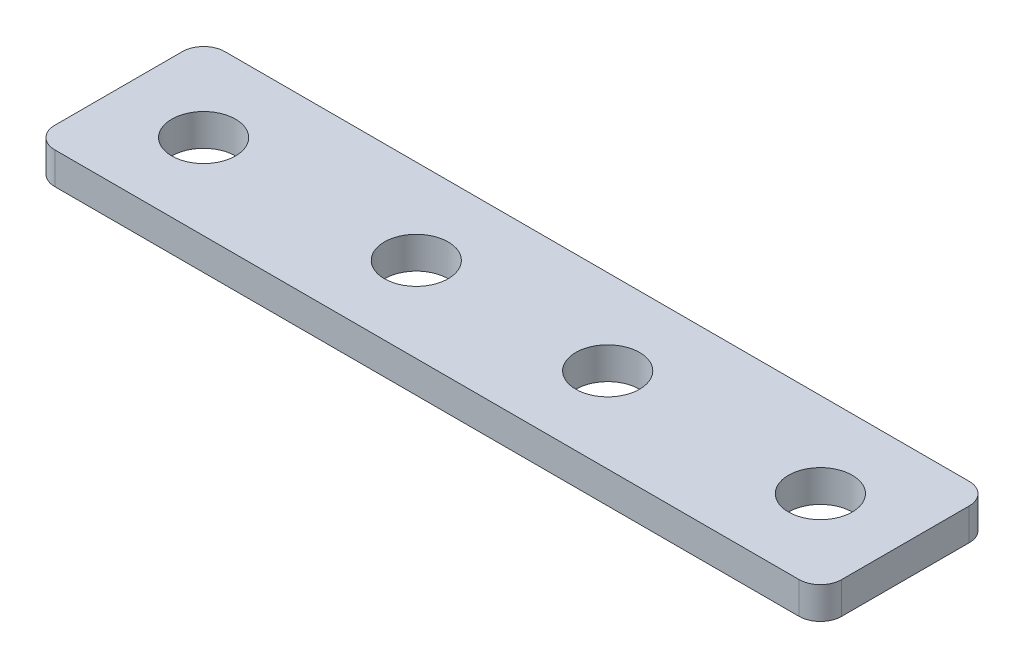
SolidWorks part; units mm, degrees
ref_plane "Front Plane" through (0, 0, 0) normal (0, 0, 1) x (1, 0, 0)
ref_plane "Top Plane" through (0, 0, 0) normal (0, 1, 0) x (1, 0, 0)
ref_plane "Right Plane" through (0, 0, 0) normal (1, 0, 0) x (0, 0, -1)
sketch "Sketch1" plane through (0, 0, 0) normal (0, 1, 0) x (1, 0, 0)
  line L0 (18.5, 8) -> (18.5, 0)
  line L1 (0, 0) -> (37, 0)
  line L2 (0, 0) -> (0, 8)
  line L3 (0, 8) -> (37, 8)
  line L4 (37, 0) -> (37, 8)
  line L5 (37, 8) -> (33, 8)
  line L6 (37, 8) -> (37, 4)
  line L7 (37, 4) -> (33, 4)
  line L8 (33, 8) -> (33, 4)
  line L9 (33, 4) -> (0, 4) construction
  circle A0 centre (33, 4) radius 1.5
  circle A1 centre (4, 4) radius 1.5
  circle A2 centre (23, 4) radius 1.5
  circle A3 centre (14, 4) radius 1.5
  dimension "D5" = 3
  dimension "D7" = 3
  dimension "D1" = 37
  dimension "D2" = 8
  dimension "D3" = 4
  dimension "D4" = 4
  dimension "D6" = 10
extrude "Boss-Extrude1" add sketch "Sketch1" along normal blind 1.5 contours L0 L9 A3 A1 L2 L1 | A0 L9 A2 L0 L1 L4 L7 | L9 L0 L3 L2 A1 A3 | L9 A0 L8 L3 L0 A2 | A0 L7 L4 L3 L8
fillet "Fillet1" radius 1 4 edges at (37, 0.75, -8) (37, 0.75, 0) (0, 0.75, -8) (0, 0.75, 0)
